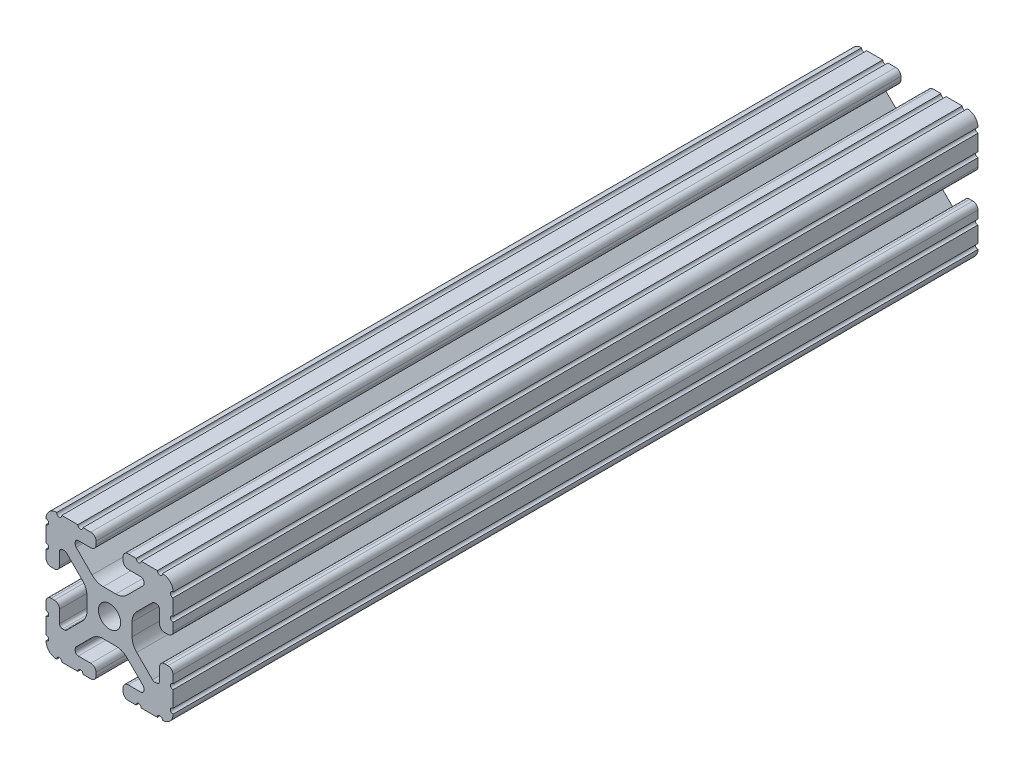
SolidWorks part; units mm, degrees
material "6061 Alloy"
ref_plane "Front Plane" through (0, 0, 0) normal (0, 0, 1) x (1, 0, 0)
ref_plane "Top Plane" through (0, 0, 0) normal (0, 1, 0) x (1, 0, 0)
ref_plane "Right Plane" through (0, 0, 0) normal (1, 0, 0) x (0, 0, -1)
sketch "Sketch1" plane through (0, 0, 0) normal (0, 0, 1) x (1, 0, 0)
  line L0 (0, 25.6181) -> (0, -24.623) construction
  line L1 (-20.8943, 0) -> (20.4607, 0) construction
  line L2 (-10.0229, 12.9148) -> (-5.2522, 8.144)
  line L3 (-10.287, 14.0843) -> (-10.287, 13.5524)
  line L4 (-5.6176, 14.986) -> (-9.3853, 14.986)
  line L5 (-4.064, 17.4964) -> (-4.064, 16.5396)
  line L6 (-7.9742, 19.05) -> (-5.6176, 19.05)
  line L7 (-14.3277, 19.05) -> (-9.4982, 19.05)
  line L8 (-19.05, 9.4961) -> (-19.05, 14.3277)
  line L9 (-19.05, 5.6176) -> (-19.05, 7.9763)
  line L10 (-16.5396, 4.064) -> (-17.4964, 4.064)
  line L11 (-14.986, 9.3853) -> (-14.986, 5.6176)
  line L12 (-13.516, 10.287) -> (-14.0843, 10.287)
  line L13 (-8.1476, 5.2921) -> (-12.8784, 10.0229)
  line L14 (-6.7564, -1.9335) -> (-6.7564, 1.9335)
  line L15 (-12.8784, -10.0229) -> (-8.1476, -5.2921)
  line L16 (-14.0843, -10.287) -> (-13.516, -10.287)
  line L17 (-14.986, -5.6176) -> (-14.986, -9.3853)
  line L18 (-17.4964, -4.064) -> (-16.5396, -4.064)
  line L19 (-19.05, -7.9763) -> (-19.05, -5.6176)
  line L20 (-19.05, -14.3277) -> (-19.05, -9.4961)
  line L21 (-9.4961, -19.05) -> (-14.3277, -19.05)
  line L22 (-5.6176, -19.05) -> (-7.9763, -19.05)
  line L23 (-4.064, -17.4964) -> (-4.064, -16.5396)
  line L24 (10.0229, -12.9148) -> (5.2522, -8.144)
  line L25 (10.287, -14.0843) -> (10.287, -13.5524)
  line L26 (5.6176, -14.986) -> (9.3853, -14.986)
  line L28 (-1.9022, 6.7564) -> (1.9022, 6.7564)
  line L29 (-1.9022, -6.7564) -> (1.9022, -6.7564)
  line L31 (-5.6176, -14.986) -> (-9.3853, -14.986)
  line L32 (-10.287, -14.0843) -> (-10.287, -13.5524)
  line L33 (-10.0229, -12.9148) -> (-5.2522, -8.144)
  line L66 (4.064, -16.5396) -> (4.064, -17.4964)
  line L67 (5.6176, -19.05) -> (7.9763, -19.05)
  line L68 (9.4961, -19.05) -> (14.3277, -19.05)
  line L69 (19.05, -14.3277) -> (19.05, -9.4961)
  line L70 (19.05, -7.9763) -> (19.05, -5.6176)
  line L71 (17.4964, -4.064) -> (16.5396, -4.064)
  line L72 (14.986, -5.6176) -> (14.986, -9.3853)
  line L73 (14.0843, -10.287) -> (13.516, -10.287)
  line L74 (12.8784, -10.0229) -> (8.1476, -5.2921)
  line L75 (6.7564, -1.9335) -> (6.7564, 1.9335)
  line L76 (8.1476, 5.2921) -> (12.8784, 10.0229)
  line L77 (13.516, 10.287) -> (14.0843, 10.287)
  line L78 (14.986, 9.3853) -> (14.986, 5.6176)
  line L79 (16.5396, 4.064) -> (17.4964, 4.064)
  line L80 (19.05, 5.6176) -> (19.05, 7.9763)
  line L81 (19.05, 9.4961) -> (19.05, 14.3277)
  line L82 (14.3277, 19.05) -> (9.4982, 19.05)
  line L83 (7.9742, 19.05) -> (5.6176, 19.05)
  line L84 (4.064, 17.4964) -> (4.064, 16.5396)
  line L85 (5.6176, 14.986) -> (9.3853, 14.986)
  line L86 (10.287, 14.0843) -> (10.287, 13.5524)
  line L87 (10.0229, 12.9148) -> (5.2522, 8.144)
  arc A0 (-10.0229, 12.9148) -> (-10.287, 13.5524) centre (-9.3853, 13.5524) cw
  circle A1 centre (0, 0) radius 3.3274
  arc A2 (-10.287, 14.0843) -> (-9.3853, 14.986) centre (-9.3853, 14.0843) cw
  arc A3 (-4.064, 16.5396) -> (-5.6176, 14.986) centre (-5.6176, 16.5396) cw
  arc A4 (-5.6176, 19.05) -> (-4.064, 17.4964) centre (-5.6176, 17.4964) cw
  arc A5 (-7.9742, 19.05) -> (-9.4982, 19.05) centre (-8.7362, 19.05) cw
  arc A6 (-14.3277, 19.05) -> (-15.8475, 19.05) centre (-15.0876, 18.9933) cw
  arc A7 (-19.05, 15.8475) -> (-15.8475, 19.05) centre (-15.8751, 15.8751) cw
  arc A8 (-19.05, 15.8475) -> (-19.05, 14.3277) centre (-18.9933, 15.0876) cw
  arc A9 (-19.05, 9.4961) -> (-19.05, 7.9763) centre (-18.9933, 8.7362) cw
  arc A10 (-17.4964, 4.064) -> (-19.05, 5.6176) centre (-17.4964, 5.6176) cw
  arc A11 (-14.986, 5.6176) -> (-16.5396, 4.064) centre (-16.5396, 5.6176) cw
  arc A12 (-14.986, 9.3853) -> (-14.0843, 10.287) centre (-14.0843, 9.3853) cw
  arc A13 (-13.516, 10.287) -> (-12.8784, 10.0229) centre (-13.516, 9.3853) cw
  arc A14 (-8.1476, 5.2921) -> (-6.7564, 1.9335) centre (-11.5062, 1.9335) cw
  arc A15 (-6.7564, -1.9335) -> (-8.1476, -5.2921) centre (-11.5062, -1.9335) cw
  arc A16 (-12.8784, -10.0229) -> (-13.516, -10.287) centre (-13.516, -9.3853) cw
  arc A17 (-14.0843, -10.287) -> (-14.986, -9.3853) centre (-14.0843, -9.3853) cw
  arc A18 (-16.5396, -4.064) -> (-14.986, -5.6176) centre (-16.5396, -5.6176) cw
  arc A19 (-19.05, -5.6176) -> (-17.4964, -4.064) centre (-17.4964, -5.6176) cw
  arc A20 (-19.05, -7.9763) -> (-19.05, -9.4961) centre (-18.9933, -8.7362) cw
  arc A21 (-19.05, -14.3277) -> (-19.05, -15.8475) centre (-18.9933, -15.0876) cw
  arc A22 (-15.8475, -19.05) -> (-19.05, -15.8475) centre (-15.8751, -15.8751) cw
  arc A23 (-15.8475, -19.05) -> (-14.3277, -19.05) centre (-15.0876, -18.9933) cw
  arc A24 (-9.4961, -19.05) -> (-7.9763, -19.05) centre (-8.7362, -18.9933) cw
  arc A25 (-4.064, -17.4964) -> (-5.6176, -19.05) centre (-5.6176, -17.4964) cw
  arc A26 (-5.2522, -8.144) -> (-1.9022, -6.7564) centre (-1.9022, -11.494) cw
  arc A27 (1.9022, -6.7564) -> (5.2522, -8.144) centre (1.9022, -11.494) cw
  arc A28 (10.0229, -12.9148) -> (10.287, -13.5524) centre (9.3853, -13.5524) cw
  arc A29 (10.287, -14.0843) -> (9.3853, -14.986) centre (9.3853, -14.0843) cw
  arc A30 (4.064, -16.5396) -> (5.6176, -14.986) centre (5.6176, -16.5396) cw
  arc A31 (-4.064, -16.5396) -> (-5.6176, -14.986) centre (-5.6176, -16.5396) ccw
  arc A32 (-10.287, -14.0843) -> (-9.3853, -14.986) centre (-9.3853, -14.0843) ccw
  arc A33 (-10.0229, -12.9148) -> (-10.287, -13.5524) centre (-9.3853, -13.5524) ccw
  arc A79 (4.064, -17.4964) -> (5.6176, -19.05) centre (5.6176, -17.4964) ccw
  arc A80 (9.4961, -19.05) -> (7.9763, -19.05) centre (8.7362, -18.9933) ccw
  arc A81 (15.8475, -19.05) -> (14.3277, -19.05) centre (15.0876, -18.9933) ccw
  arc A82 (15.8475, -19.05) -> (19.05, -15.8475) centre (15.8751, -15.8751) ccw
  arc A83 (19.05, -14.3277) -> (19.05, -15.8475) centre (18.9933, -15.0876) ccw
  arc A84 (19.05, -7.9763) -> (19.05, -9.4961) centre (18.9933, -8.7362) ccw
  arc A85 (19.05, -5.6176) -> (17.4964, -4.064) centre (17.4964, -5.6176) ccw
  arc A86 (16.5396, -4.064) -> (14.986, -5.6176) centre (16.5396, -5.6176) ccw
  arc A87 (14.0843, -10.287) -> (14.986, -9.3853) centre (14.0843, -9.3853) ccw
  arc A88 (12.8784, -10.0229) -> (13.516, -10.287) centre (13.516, -9.3853) ccw
  arc A89 (6.7564, -1.9335) -> (8.1476, -5.2921) centre (11.5062, -1.9335) ccw
  arc A90 (8.1476, 5.2921) -> (6.7564, 1.9335) centre (11.5062, 1.9335) ccw
  arc A91 (13.516, 10.287) -> (12.8784, 10.0229) centre (13.516, 9.3853) ccw
  arc A92 (14.986, 9.3853) -> (14.0843, 10.287) centre (14.0843, 9.3853) ccw
  arc A93 (14.986, 5.6176) -> (16.5396, 4.064) centre (16.5396, 5.6176) ccw
  arc A94 (17.4964, 4.064) -> (19.05, 5.6176) centre (17.4964, 5.6176) ccw
  arc A95 (19.05, 9.4961) -> (19.05, 7.9763) centre (18.9933, 8.7362) ccw
  arc A96 (19.05, 15.8475) -> (19.05, 14.3277) centre (18.9933, 15.0876) ccw
  arc A97 (19.05, 15.8475) -> (15.8475, 19.05) centre (15.8751, 15.8751) ccw
  arc A98 (14.3277, 19.05) -> (15.8475, 19.05) centre (15.0876, 18.9933) ccw
  arc A99 (7.9742, 19.05) -> (9.4982, 19.05) centre (8.7362, 19.05) ccw
  arc A100 (5.6176, 19.05) -> (4.064, 17.4964) centre (5.6176, 17.4964) ccw
  arc A101 (4.064, 16.5396) -> (5.6176, 14.986) centre (5.6176, 16.5396) ccw
  arc A102 (10.287, 14.0843) -> (9.3853, 14.986) centre (9.3853, 14.0843) ccw
  arc A103 (10.0229, 12.9148) -> (10.287, 13.5524) centre (9.3853, 13.5524) ccw
  arc A104 (1.9022, 6.7564) -> (5.2522, 8.144) centre (1.9022, 11.494) ccw
  arc A105 (-5.2522, 8.144) -> (-1.9022, 6.7564) centre (-1.9022, 11.494) ccw
  dimension "D1" = 6.6548
  dimension "D2" = 19.05
  dimension "D3" = 38.1
  dimension "D4" = 20.574
  dimension "D5" = 13.5128
  dimension "D6" = 4.064
  dimension "D7" = 8.128
  dimension "D8" = 4.064
  dimension "D9" = 12.2936
extrude "Extrude1" add sketch "Sketch1" against normal blind 241.3
